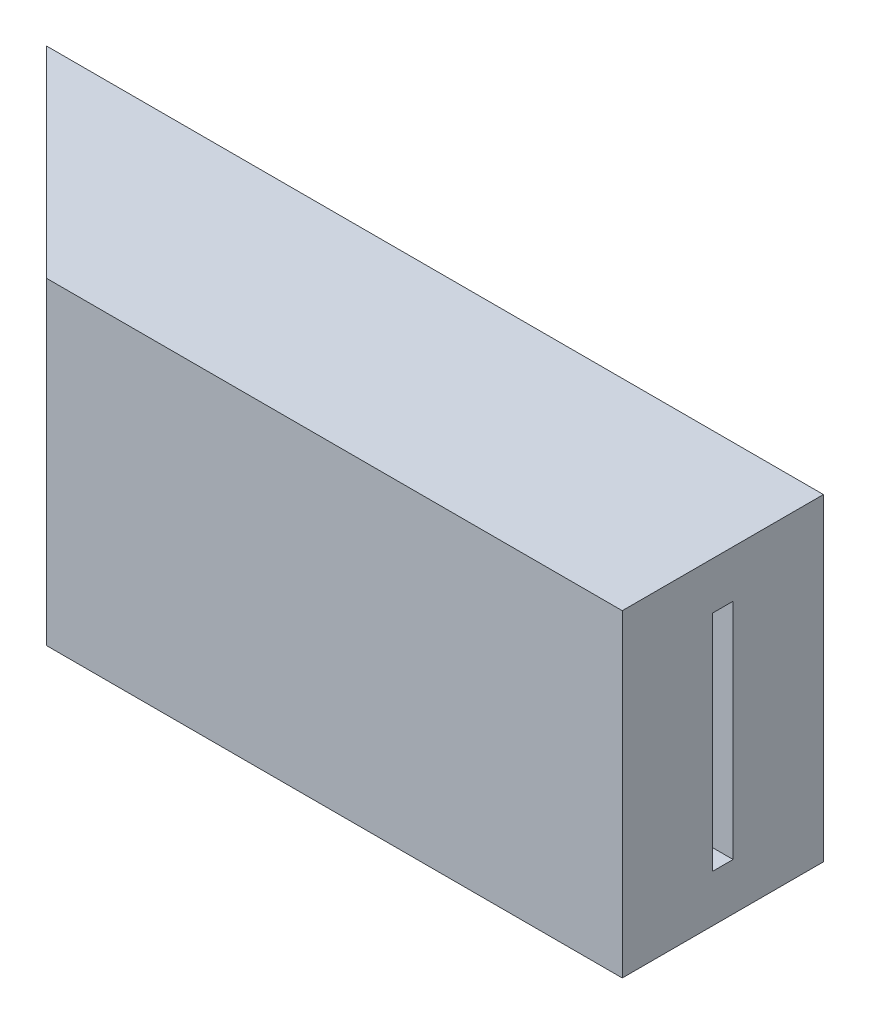
SolidWorks part; units mm, degrees
ref_plane "Alzado" through (0, 0, 0) normal (0, 0, 1) x (1, 0, 0)
ref_plane "Planta" through (0, 0, 0) normal (0, 1, 0) x (1, 0, 0)
ref_plane "Vista lateral" through (0, 0, 0) normal (1, 0, 0) x (0, 0, -1)
ref_plane "Plano1" through (0, 19.7612, 0) normal (0, 1, 0) x (1, 0, 0)
sketch "Croquis1" plane through (0, 19.7612, 0) normal (0, 1, 0) x (1, 0, 0)
  line L0 (0, 12.4968) -> (24.9936, -12.4968)
  line L1 (24.9936, -12.4968) -> (24.9936, 12.4968)
  line L2 (24.9936, 12.4968) -> (0, 12.4968)
extrude "Saliente-Extruir1" add sketch "Croquis1" against normal blind 37.5285
sketch "Croquis2" plane through (0, -17.7673, 0) normal (0, -1, 0) x (1, 0, 0)
  line L0 (24.9936, -10.5029) -> (24.9936, 10.5029)
  line L1 (24.9936, 10.5029) -> (22.9997, 10.5029)
  line L2 (22.9997, 10.5029) -> (1.9939, -10.5029)
  line L3 (1.9939, -10.5029) -> (24.9936, -10.5029)
extrude "Cortar-Extruir1" cut sketch "Croquis2" against normal blind 18.4023
sketch "Croquis3" plane through (24.9936, 0, 0) normal (1, 0, 0) x (0, 0, -1)
  line L0 (10.5029, -17.7673) -> (10.5029, 0.635)
  line L1 (10.5029, 0.635) -> (-10.5029, 0.635)
  line L2 (-10.5029, 0.635) -> (-10.5029, -17.7673)
  line L3 (-10.5029, -17.7673) -> (-12.4968, -17.7673)
  line L4 (-12.4968, -17.7673) -> (-12.4968, 19.7612)
  line L5 (-12.4968, 19.7612) -> (12.4968, 19.7612)
  line L6 (12.4968, 19.7612) -> (12.4968, -17.7673)
  line L7 (12.4968, -17.7673) -> (10.5029, -17.7673)
extrude "Saliente-Extruir2" add sketch "Croquis3" along normal blind 15.0114
sketch "Croquis4" plane through (40.005, 0, 0) normal (1, 0, 0) x (0, 0, -1)
  line L0 (10.5029, 1.47) -> (-10.5029, 1.47)
  line L1 (-10.5029, 1.47) -> (-10.5029, -17.7673)
  line L2 (-10.5029, -17.7673) -> (-12.4968, -17.7673)
  line L3 (-12.4968, -17.7673) -> (-12.4968, 19.7612)
  line L4 (-12.4968, 19.7612) -> (12.4968, 19.7612)
  line L5 (12.4968, 19.7612) -> (12.4968, -17.7673)
  line L6 (12.4968, -17.7673) -> (10.5029, -17.7673)
  line L7 (10.5029, -17.7673) -> (10.5029, 1.47)
extrude "Saliente-Extruir3" add sketch "Croquis4" along normal blind 53.975
sketch "Croquis5" plane through (0, 0.635, 0) normal (0, -1, 0) x (1, 0, 0)
  line L0 (93.98, -10.5029) -> (93.98, 10.5029)
  line L1 (93.98, 10.5029) -> (22.9997, 10.5029)
  line L2 (22.9997, 10.5029) -> (1.9939, -10.5029)
  line L3 (1.9939, -10.5029) -> (93.98, -10.5029)
extrude "Cortar-Extruir2" cut sketch "Croquis5" against normal blind 17.1323
sketch "Croquis6" plane through (93.98, 0, 0) normal (1, 0, 0) x (0, 0, -1)
  line L4 (-12.4968, -17.7673) -> (-12.4968, 19.7612)
  line L5 (-12.4968, 19.7612) -> (12.4968, 19.7612)
  line L6 (12.4968, 19.7612) -> (12.4968, -17.7673)
  line L7 (12.4968, -17.7673) -> (-12.4968, -17.7673)
  line L8 (-1.27, -13.8938) -> (1.27, -13.8938)
  line L9 (1.27, -13.8938) -> (1.27, 13.8962)
  line L10 (1.27, 13.8962) -> (-1.27, 13.8962)
  line L11 (-1.27, 13.8962) -> (-1.27, -13.8938)
  dimension "D1" = 27.79
extrude "Saliente-Extruir4" add sketch "Croquis6" along normal blind 2.54
sketch "Croquis7" plane through (0, -17.7673, 0) normal (0, -1, 0) x (1, 0, 0)
  line L0 (24.9936, 12.4968) -> (96.52, 12.4968)
  line L1 (96.52, 12.4968) -> (96.52, -12.4968)
  line L2 (96.52, -12.4968) -> (0, -12.4968)
  line L3 (0, -12.4968) -> (24.9936, 12.4968)
extrude "Saliente-Extruir5" add sketch "Croquis7" along normal blind 1.9939
sketch "Croquis8" plane through (0, -17.7673, 0) normal (0, 1, 0) x (-1, 0, 0)
  line L0 (-65.405, -4.1382) -> (-65.405, -10.5029)
  line L1 (-65.405, -10.5029) -> (-68.58, -10.5029)
  line L2 (-68.58, -10.5029) -> (-68.58, -3.8195)
  line L3 (-68.58, -3.8195) -> (-65.405, -4.1382)
sketch "Croquis14" plane through (0, 19.7612, 0) normal (0, 1, 0) x (1, 0, 0)
  line L0 (24.9936, -12.4968) -> (24.9936, 12.4968)
  line L1 (96.52, 12.4968) -> (0, 12.4968) construction
extrude "Saliente-Extruir6" add sketch "Croquis8" along normal blind 17.1323
sketch "Croquis9" plane through (0, 17.7673, 0) normal (0, -1, 0) x (1, 0, 0)
  line L0 (65.405, 10.5029) -> (68.58, 10.5029)
  line L1 (68.58, 10.5029) -> (68.58, 4.574)
  line L2 (68.58, 4.574) -> (65.405, 4.9869)
  line L3 (65.405, 4.9869) -> (65.405, 10.5029)
extrude "Saliente-Extruir7" add sketch "Croquis9" along normal blind 18.683
sketch "Croquis10" plane through (0, 17.7673, 0) normal (0, -1, 0) x (1, 0, 0)
  line L0 (68.58, -3.8195) -> (68.58, -10.5029)
  line L1 (68.58, -10.5029) -> (65.405, -10.5029)
  line L2 (65.405, -10.5029) -> (65.405, -4.1382)
  line L3 (65.405, -4.1382) -> (68.58, -3.8195)
extrude "Saliente-Extruir8" add sketch "Croquis10" along normal blind 19.016
sketch "Croquis11" plane through (0, -17.7673, 0) normal (0, 1, 0) x (-1, 0, 0)
  line L0 (-68.58, 10.5029) -> (-65.405, 10.5029)
  line L1 (-65.405, 10.5029) -> (-65.405, 4.9869)
  line L2 (-65.405, 4.9869) -> (-68.58, 4.574)
  line L3 (-68.58, 4.574) -> (-68.58, 10.5029)
extrude "Saliente-Extruir9" add sketch "Croquis11" along normal blind 17.1323
chamfer "Chaflán1" distance 2.54 angle 45 7 edges at (44.2024, 17.7673, 10.5029) (33.6995, -17.7673, -10.5029) (33.6994, 17.7673, -10.5029) (81.28, 17.7673, 10.5029) (44.2024, -17.7673, 10.5029) (81.28, -17.7673, 10.5029) (81.28, 17.7673, -10.5029)
